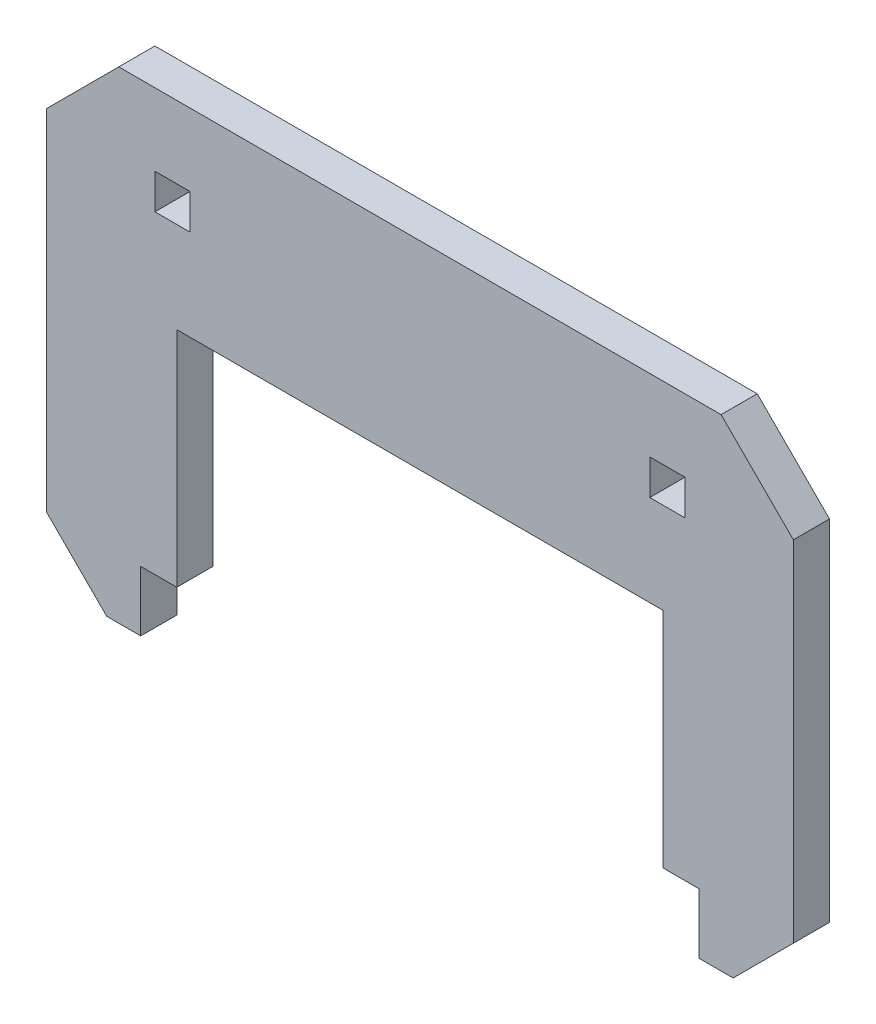
SolidWorks part; units mm, degrees
ref_plane "Front Plane" through (0, 0, 0) normal (0, 0, 1) x (1, 0, 0)
ref_plane "Top Plane" through (0, 0, 0) normal (0, 1, 0) x (1, 0, 0)
ref_plane "Right Plane" through (0, 0, 0) normal (1, 0, 0) x (0, 0, -1)
sketch "Sketch1" plane through (0, 0, 0) normal (0, 0, 1) x (1, 0, 0)
  line L0 (22.1346, 14.538) -> (28.1346, 8.538)
  line L1 (-33.8654, 14.538) -> (28.1346, 14.538)
  line L2 (-33.8654, 14.538) -> (-33.8654, -25.462)
  line L3 (23.1346, -25.462) -> (20.3146, -25.462)
  line L4 (28.1346, 14.538) -> (28.1346, -25.462)
  line L5 (-2.8654, 14.538) -> (-2.8654, 26.2114) construction
  line L6 (28.1346, -20.462) -> (23.1346, -25.462)
  line L7 (20.3146, -25.462) -> (20.3146, -20.462)
  line L8 (20.3146, -20.462) -> (17.3146, -20.462)
  line L9 (17.3146, -20.462) -> (17.3146, -1.942)
  line L10 (-23.0454, -1.942) -> (17.3146, -1.942)
  line L11 (16.2146, 8.538) -> (19.1346, 8.538)
  line L12 (16.2146, 8.538) -> (16.2146, 5.618)
  line L13 (16.2146, 5.618) -> (19.1346, 5.618)
  line L14 (19.1346, 8.538) -> (19.1346, 5.618)
  line L15 (-27.8654, 14.538) -> (-33.8654, 8.538)
  line L16 (-33.8654, -20.462) -> (-28.8654, -25.462)
  line L17 (-24.8654, 8.538) -> (-24.8654, 5.618)
  line L18 (-21.9454, 5.618) -> (-24.8654, 5.618)
  line L19 (-21.9454, 8.538) -> (-21.9454, 5.618)
  line L20 (-21.9454, 8.538) -> (-24.8654, 8.538)
  line L21 (-23.0454, -20.462) -> (-23.0454, -1.942)
  line L22 (-26.0454, -20.462) -> (-23.0454, -20.462)
  line L23 (-26.0454, -25.462) -> (-26.0454, -20.462)
  line L24 (-28.8654, -25.462) -> (-26.0454, -25.462)
  point P28 (-2.8654, -1.942)
  dimension "D1" = 62
  dimension "D2" = 40
  dimension "D3" = 6
  dimension "D4" = 6
  dimension "D5" = 5
  dimension "D6" = 5
  dimension "D7" = 2.82
  dimension "D8" = 5
  dimension "D9" = 3
  dimension "D10" = 2.92
  dimension "D11" = 2.92
  dimension "D12" = 6
  dimension "D13" = 9
  dimension "D14" = 18.52
extrude "Boss-Extrude1" add sketch "Sketch1" along normal blind 3 contours L16 L24 L23 L22 L21 L10 L9 L8 L7 L3 L6 L4 L0 L1 L15 L2 L11 L14 L13 L12 L20 L19 L18 L17
